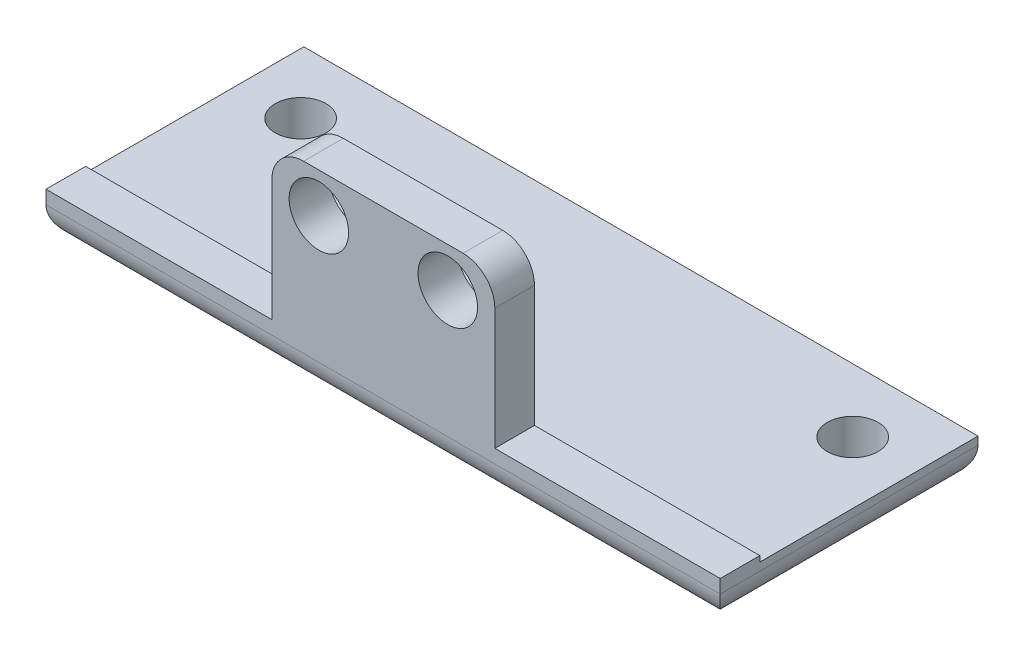
SolidWorks part; units mm, degrees
ref_plane "Plan de face" through (0, 0, 0) normal (0, 0, 1) x (1, 0, 0)
ref_plane "Plan de dessus" through (0, 0, 0) normal (0, 1, 0) x (1, 0, 0)
ref_plane "Plan de droite" through (0, 0, 0) normal (1, 0, 0) x (0, 0, -1)
sketch "Esquisse1" plane through (0, 0, 0) normal (0, 1, 0) x (1, 0, 0)
  line L1 (0, 0) -> (53.975, 0)
  line L2 (0, 0) -> (0, 12.7)
  line L3 (0, 12.7) -> (53.975, 12.7)
  line L4 (53.975, 0) -> (53.975, 12.7)
  dimension "D1" = 12.7
  dimension "D2" = 53.975
extrude "Boss.-Extru.1" add sketch "Esquisse1" along normal blind 3.175
sketch "Esquisse2" plane through (0, 3.175, 0) normal (0, 1, 0) x (1, 0, 0)
  line L2 (53.975, 0) -> (53.975, 12.7) construction
  line L3 (53.975, 12.7) -> (0, 12.7) construction
  circle A0 centre (4.826, 7.62) radius 2.032
  circle A1 centre (49.022, 7.62) radius 2.032
  dimension "D1" = 4.064
  dimension "D2" = 4.064
  dimension "D3" = 44.196
  dimension "D4" = 4.953
  dimension "D5" = 5.08
  dimension "D6" = 5.08
extrude "Enlèv. mat.-Extru.1" cut sketch "Esquisse2" against normal blind 3.175
sketch "Esquisse3" plane through (0, 3.175, 0) normal (0, 1, 0) x (1, 0, 0)
  line L0 (0, 12.7) -> (0, 0) construction
  line L1 (0, 0) -> (53.975, 0)
  line L2 (0, 0) -> (0, -7.9375)
  line L3 (0, -7.9375) -> (53.975, -7.9375)
  line L4 (53.975, 0) -> (53.975, -7.9375)
  line L5 (53.975, 0) -> (53.975, 12.7) construction
  dimension "D1" = 20.6375
extrude "Boss.-Extru.2" add sketch "Esquisse3" against normal blind 3.175
sketch "Esquisse4" plane through (0, 3.175, 0) normal (0, 1, 0) x (1, 0, 0)
  line L0 (53.975, -7.9375) -> (53.975, 12.7) construction
  line L1 (0, -7.9375) -> (53.975, -7.9375)
  line L2 (0, -7.9375) -> (0, -4.7625)
  line L3 (0, -4.7625) -> (53.975, -4.7625)
  line L4 (53.975, -7.9375) -> (53.975, -4.7625)
  dimension "D1" = 3.175
extrude "Boss.-Extru.3" add sketch "Esquisse4" along normal blind 12.7
sketch "Esquisse5" plane through (0, 0, 7.9375) normal (0, 0, 1) x (1, 0, 0)
  line L0 (0, 15.875) -> (53.975, 15.875) construction
  line L2 (0, 0) -> (0, 15.875) construction
  circle A0 centre (21.844, 12.7) radius 2.3813
  circle A1 centre (32.1627, 12.7) radius 2.3812
  dimension "D5" = 4.7625
  dimension "D6" = 4.7625
  dimension "D1" = 10.3187
  dimension "D2" = 3.175
  dimension "D3" = 3.175
  dimension "D4" = 21.844
extrude "Enlèv. mat.-Extru.2" cut sketch "Esquisse5" against normal blind 12.7
sketch "Esquisse6" plane through (0, 0, 7.9375) normal (0, 0, 1) x (1, 0, 0)
  line L0 (0, 15.875) -> (53.975, 15.875) construction
  line L1 (0, 15.875) -> (18.0842, 15.875)
  line L2 (0, 15.875) -> (0, 3.6207)
  line L3 (0, 3.6207) -> (18.0842, 3.6207)
  line L4 (18.0842, 15.875) -> (18.0842, 3.6207)
  line L5 (0, 0) -> (0, 15.875) construction
  line L7 (53.975, 15.875) -> (35.9307, 15.875)
  line L8 (53.975, 15.875) -> (53.975, 3.6207)
  line L9 (53.975, 3.6207) -> (35.9307, 3.6207)
  line L10 (35.9307, 15.875) -> (35.9307, 3.6207)
extrude "Enlèv. mat.-Extru.3" cut sketch "Esquisse6" against normal blind 12.7
fillet "Congé2" radius 2.54 6 edges at (26.9875, 0, 7.9375) (53.975, 0, -2.3812) (26.9875, 0, -12.7) (0, 0, -2.3812) (35.9307, 15.875, 6.35) (18.0842, 15.875, 6.35)
